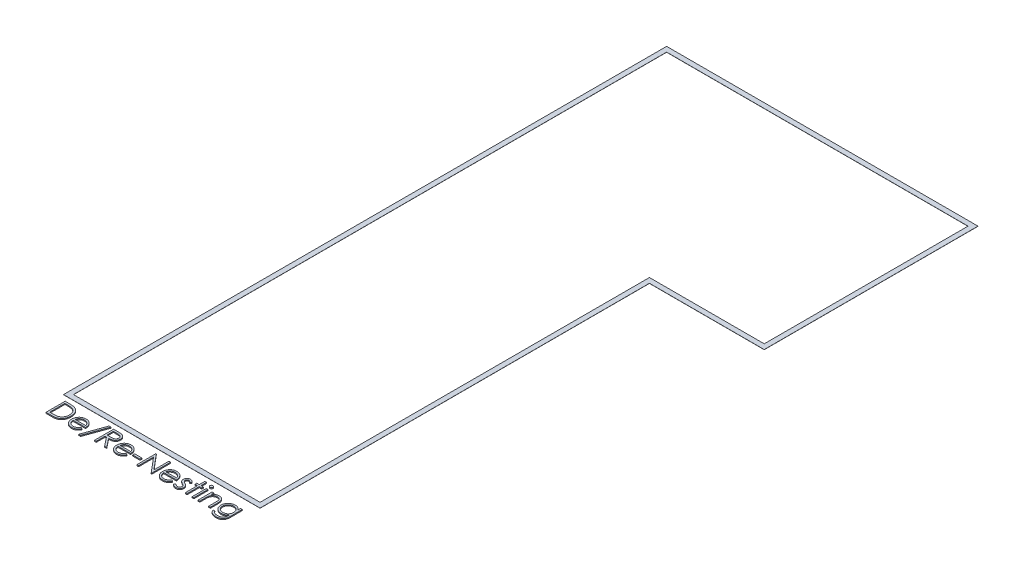
SolidWorks part; units mm, degrees
ref_plane "Front Plane" through (0, 0, 0) normal (0, 0, 1) x (1, 0, 0)
ref_plane "Top Plane" through (0, 0, 0) normal (0, 1, 0) x (1, 0, 0)
ref_plane "Right Plane" through (0, 0, 0) normal (1, 0, 0) x (0, 0, -1)
sketch "Sketch1" plane through (0, 0, 0) normal (0, 1, 0) x (1, 0, 0)
  line L0 (-307.0255, 600.1655) -> (-307.0255, -599.8345) construction
  line L1 (-307.0255, -599.8345) -> (77.3803, -599.8345) construction
  line L2 (77.3803, -599.8345) -> (77.3803, 181.3025) construction
  line L3 (77.3803, 181.3025) -> (307.6875, 181.3025) construction
  line L4 (307.6875, 181.3025) -> (307.6875, 600.1655) construction
  line L5 (307.6875, 600.1655) -> (-307.0255, 600.1655) construction
  line L6 (-312.0255, 605.1655) -> (-312.0255, -604.8345)
  line L7 (-312.0255, -604.8345) -> (82.3803, -604.8345)
  line L8 (82.3803, -604.8345) -> (82.3803, 176.3025)
  line L9 (82.3803, 176.3025) -> (312.6875, 176.3025)
  line L10 (312.6875, 176.3025) -> (312.6875, 605.1655)
  line L11 (312.6875, 605.1655) -> (-312.0255, 605.1655)
  line L12 (-302.0255, 595.1655) -> (-302.0255, -594.8345)
  line L13 (-302.0255, -594.8345) -> (72.3803, -594.8345)
  line L14 (72.3803, -594.8345) -> (72.3803, 186.3025)
  line L15 (72.3803, 186.3025) -> (302.6875, 186.3025)
  line L16 (302.6875, 186.3025) -> (302.6875, 595.1655)
  line L17 (302.6875, 595.1655) -> (-302.0255, 595.1655)
  dimension "D1" = 5
  dimension "D2" = 5
extrude "Boss-Extrude1" add sketch "Sketch1" along normal blind 0.3
sketch "Sketch2" plane through (0, 0, 0) normal (0, 1, 0) x (1, 0, 0)
  line L0 (-302.0255, -654.8345) -> (72.3803, -654.8345) construction
  line L1 (-302.0255, 595.1655) -> (-302.0255, -594.8345) construction
  line L2 (72.3803, -594.8345) -> (72.3803, 186.3025) construction
  line L4 (-312.0255, -604.8345) -> (82.3803, -604.8345) construction
  text T0 "De/Re-Nesting" font "Century Gothic" height 38.5
  dimension "D1" = 50
extrude "Boss-Extrude2" add sketch "Sketch2" along normal blind 2
